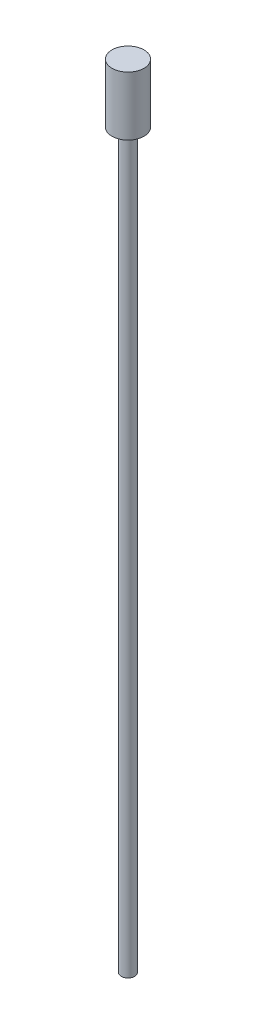
SolidWorks part; units mm, degrees
ref_plane "Plan de face" through (0, 0, 0) normal (0, 0, 1) x (1, 0, 0)
ref_plane "Plan de dessus" through (0, 0, 0) normal (0, 1, 0) x (1, 0, 0)
ref_plane "Plan de droite" through (0, 0, 0) normal (1, 0, 0) x (0, 0, -1)
sketch "Esquisse1" plane through (0, 0, 0) normal (0, 1, 0) x (1, 0, 0)
  circle A0 centre (0, 0) radius 4
  dimension "D1" = 8
extrude "Boss.-Extru.1" add sketch "Esquisse1" along normal blind 435
sketch "Esquisse2" plane through (0, 435, 0) normal (0, 1, 0) x (1, 0, 0)
  circle A0 centre (0, 0) radius 9.5
  dimension "D1" = 19
extrude "Boss.-Extru.2" add sketch "Esquisse2" along normal blind 35
